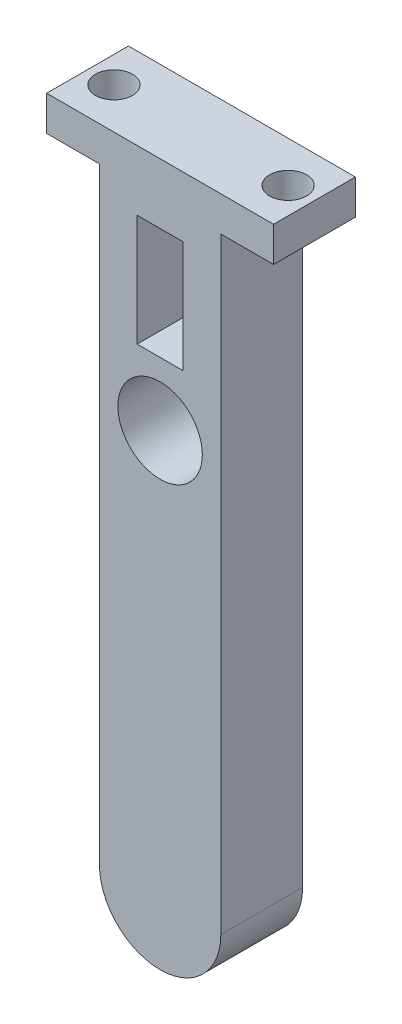
SolidWorks part; units mm, degrees
ref_plane "Piano frontale" through (0, 0, 0) normal (0, 0, 1) x (1, 0, 0)
ref_plane "Piano superiore" through (0, 0, 0) normal (0, 1, 0) x (1, 0, 0)
ref_plane "Piano destro" through (0, 0, 0) normal (1, 0, 0) x (0, 0, -1)
sketch "Schizzo3" plane through (0, 0, 0) normal (0, 0, 1) x (1, 0, 0)
  line L0 (-62.6021, -3.8591) -> (-62.6021, 111.1409)
  line L1 (-62.6021, 111.1409) -> (-72.6021, 111.1409)
  line L2 (-72.6021, 111.1409) -> (-72.6021, 117.7409)
  line L3 (-72.6021, 117.7409) -> (-29.6021, 117.7409)
  line L4 (-29.6021, 117.7409) -> (-29.6021, 111.1409)
  line L5 (-29.6021, 111.1409) -> (-39.6021, 111.1409)
  line L6 (-39.6021, 111.1409) -> (-39.6021, -3.8591)
  arc A0 (-62.6021, -3.8591) -> (-39.6021, -3.8591) centre (-51.1021, -3.8591) ccw
  dimension "D1" = 43
  dimension "D2" = 23
sketch "Schizzo6" plane through (0, 0, 0) normal (0, 0, 1) x (1, 0, 0)
  line L11 (-62.6021, 111.1409) -> (-39.6021, 111.1409)
  circle A0 centre (-51.1021, 73.1409) radius 8
  point P0 (-51.1021, 111.1409)
  dimension "D1" = 38
sketch "Schizzo7" plane through (0, 0, 0) normal (0, 0, 1) x (1, 0, 0)
  line L0 (-39.6021, 111.1409) -> (-39.6021, -3.8591) construction
  line L1 (-55.4521, 106.2874) -> (-46.7521, 106.2874)
  line L2 (-55.4521, 106.2874) -> (-55.4521, 85.1409)
  line L3 (-55.4521, 85.1409) -> (-46.7521, 85.1409)
  line L4 (-46.7521, 106.2874) -> (-46.7521, 85.1409)
  line L6 (-62.6021, -3.8591) -> (-62.6021, 111.1409) construction
  point P9 (-51.1021, 85.1409)
  dimension "D1" = 7.15
  dimension "D2" = 7.15
  dimension "D3" = 12
extrude "Estrusione-Estrusione3" add sketch "Schizzo3" along normal blind 15.5 contours L0 L1 L2 L3 L4 L5 L6 A0
extrude "Taglio-Estrusione1" cut sketch "Schizzo6" along normal blind 15.5 contours A0
extrude "Taglio-Estrusione2" cut sketch "Schizzo7" along normal blind 15.5 contours L1 L4 L3 L2
sketch "Schizzo14" plane through (0, 111.1409, 0) normal (0, -1, 0) x (-1, 0, 0)
  circle A0 centre (34.6021, -7.75) radius 3.5
  point P14 (34.6021, -7.75)
extrude "Taglio-Estrusione3" cut sketch "Schizzo14" against normal blind 6.6 contours A0
sketch "Schizzo15" plane through (0, 111.1409, 0) normal (0, -1, 0) x (-1, 0, 0)
  circle A0 centre (67.6021, -7.75) radius 3.5
  point P14 (67.6021, -7.75)
extrude "Taglio-Estrusione4" cut sketch "Schizzo15" against normal blind 6.6 contours A0
